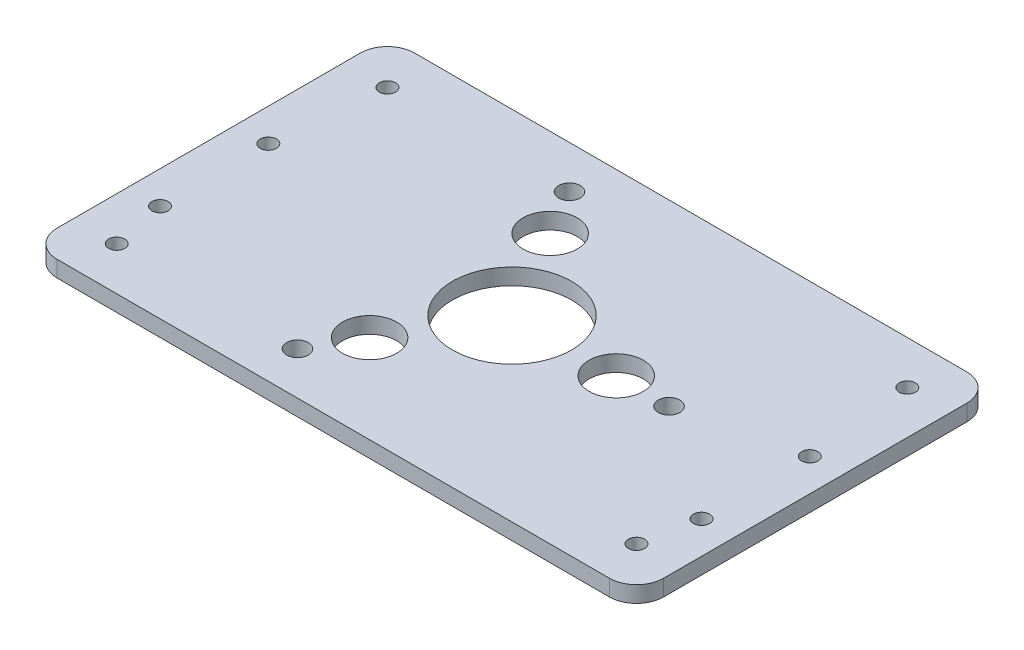
SolidWorks part; units mm, degrees
ref_plane "前视基准面" through (0, 0, 0) normal (0, 0, 1) x (1, 0, 0)
ref_plane "上视基准面" through (0, 0, 0) normal (0, 1, 0) x (1, 0, 0)
ref_plane "右视基准面" through (0, 0, 0) normal (1, 0, 0) x (0, 0, -1)
other "Configuration Table"
sketch "草图1" plane through (0, 0, 0) normal (0, 1, 0) x (1, 0, 0)
  line L0 (0, 0) -> (56, 0) construction
  line L1 (-56, 33) -> (56, 33)
  line L2 (-56, 33) -> (-56, -33)
  line L3 (-56, -33) -> (56, -33)
  line L4 (56, 33) -> (56, -33)
  line L5 (-56, 33) -> (56, -33) construction
  line L6 (-56, -33) -> (56, 33) construction
  line L7 (0, 0) -> (0, 33) construction
  line L8 (50, 5) -> (50, -15) construction
  line L9 (-50, -15) -> (-50, 5) construction
  circle A0 centre (-50, 5) radius 1.5
  circle A1 centre (-50, -15) radius 1.5
  circle A2 centre (50, -15) radius 1.5
  circle A3 centre (50, 5) radius 1.5
  circle A4 centre (-14.5, 25.1147) radius 2
  circle A5 centre (29, 0) radius 2
  circle A6 centre (-14.5, -25.1147) radius 2
  circle A9 centre (0, 0) radius 29 construction
  circle A11 centre (0, 0) radius 11
  circle A15 centre (19.25, 0) radius 5
  circle A16 centre (-9.625, -16.671) radius 5
  circle A17 centre (-9.625, 16.671) radius 5
  point P0 (0, 0)
  point P25 (0, 0)
  point P34 (0, 0)
  dimension "D6" = 4
  dimension "D8" = 58
  dimension "D9" = 19.25
  dimension "D10" = 22
  dimension "D11" = 10
  dimension "D3" = 3
  dimension "D2" = 66
  dimension "D4" = 100
  dimension "D12" = 3
  dimension "D14" = 20
  dimension "D15" = 5
  dimension "D16" = 6
  dimension "D7" = 3
extrude "凸台-拉伸1" add sketch "草图1" along normal blind 3
fillet "圆角1" radius 5 4 edges at (56, 1.5, 33) (-56, 1.5, -33) (56, 1.5, -33) (-56, 1.5, 33)
sketch "草图2" plane through (0, 3, 0) normal (0, 1, 0) x (1, 0, 0)
  line L0 (0, 0) -> (56, 0) construction
  line L1 (56, -28) -> (56, 28) construction
  line L2 (51, 33) -> (-51, 33) construction
  line L3 (0, 0) -> (0, 33) construction
  line L4 (-56, 28) -> (-56, -28) construction
  circle A0 centre (-48, 25) radius 1.5
  circle A1 centre (-48, -25) radius 1.5
  circle A2 centre (48, -25) radius 1.5
  circle A3 centre (48, 25) radius 1.5
  dimension "D2" = 3
  dimension "D1" = 8
  dimension "D3" = 8
extrude "切除-拉伸1" cut sketch "草图2" against normal blind 10
